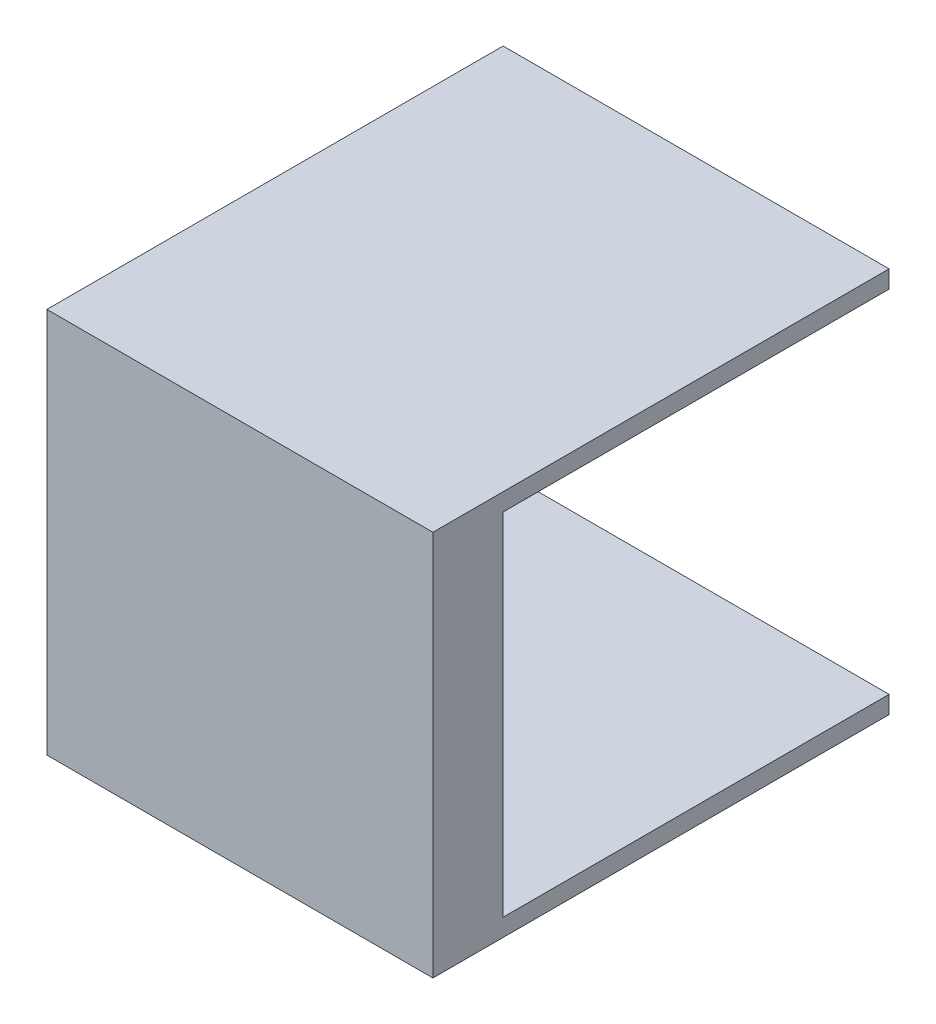
SolidWorks part; units mm, degrees
ref_plane "前视基准面" through (0, 0, 0) normal (0, 0, 1) x (1, 0, 0)
ref_plane "上视基准面" through (0, 0, 0) normal (0, 1, 0) x (1, 0, 0)
ref_plane "右视基准面" through (0, 0, 0) normal (1, 0, 0) x (0, 0, -1)
sketch "草图1" plane through (0, 0, 0) normal (0, 0, 1) x (1, 0, 0)
  line L1 (-55, 55) -> (55, 55)
  line L2 (-55, 55) -> (-55, -55)
  line L3 (-55, -55) -> (55, -55)
  line L4 (55, 55) -> (55, -55)
  line L5 (-55, 55) -> (55, -55) construction
  line L6 (-55, -55) -> (55, 55) construction
  point P0 (0, 0)
  dimension "D1" = 110
  dimension "D2" = 110
extrude "凸台-拉伸1" add sketch "草图1" along normal blind 130
sketch "草图2" plane through (0, 0, 0) normal (0, 0, -1) x (-1, 0, 0)
  line L1 (-50, 50) -> (50, 50)
  line L2 (-50, 50) -> (-50, -50)
  line L3 (-50, -50) -> (50, -50)
  line L4 (50, 50) -> (50, -50)
  line L5 (-50, 50) -> (50, -50) construction
  line L6 (-50, -50) -> (50, 50) construction
  point P0 (0, 0)
  dimension "D1" = 100
  dimension "D2" = 100
extrude "切除-拉伸1" cut sketch "草图2" against normal blind 110
sketch "草图3" plane through (55, 0, 0) normal (1, 0, 0) x (0, 0, -1)
  line L0 (0, 50) -> (-110, 50)
  line L1 (0, -55) -> (0, 55) construction
  line L2 (-110, 50) -> (-110, -50)
  line L3 (-110, -50) -> (0, -50)
  line L4 (-130, -55) -> (0, -55) construction
  dimension "D1" = 100
  dimension "D2" = 5
  dimension "D3" = 110
extrude "切除-拉伸2" cut sketch "草图3" against normal blind 10 and the other way through all
